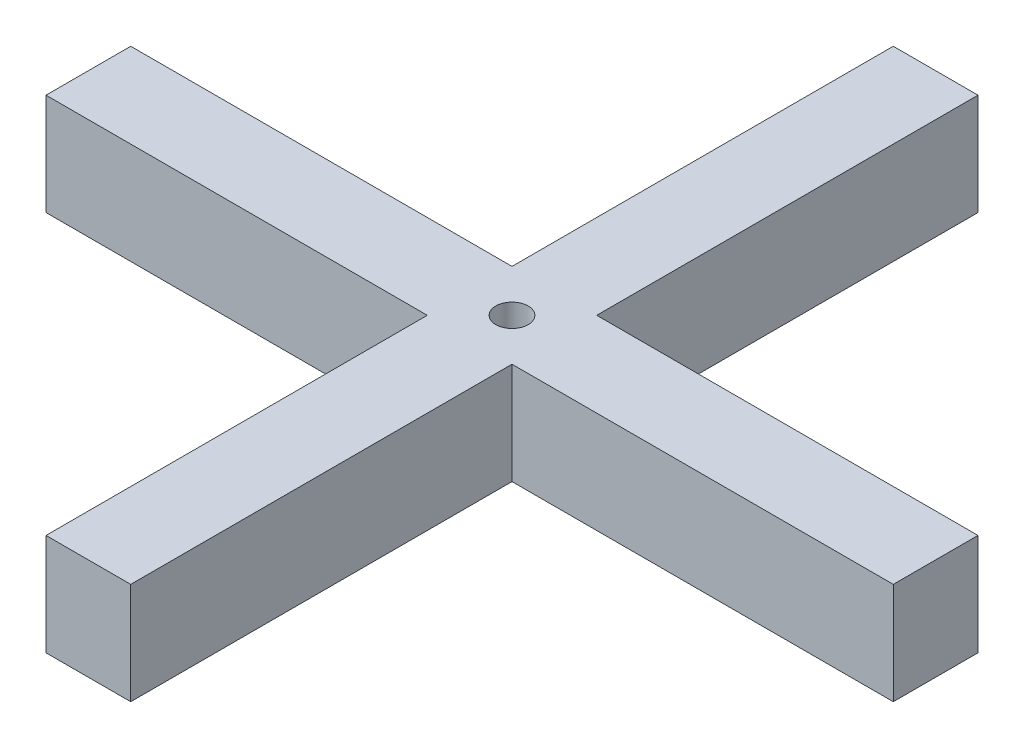
SolidWorks part; units mm, degrees
ref_plane "Front Plane" through (0, 0, 0) normal (0, 0, 1) x (1, 0, 0)
ref_plane "Top Plane" through (0, 0, 0) normal (0, 1, 0) x (1, 0, 0)
ref_plane "Right Plane" through (0, 0, 0) normal (1, 0, 0) x (0, 0, -1)
sketch "Sketch1" plane through (0, 0, 0) normal (0, 1, 0) x (1, 0, 0)
  line L1 (-31.75, 3.175) -> (31.75, 3.175)
  line L2 (-31.75, 3.175) -> (-31.75, -3.175)
  line L3 (-31.75, -3.175) -> (31.75, -3.175)
  line L4 (31.75, 3.175) -> (31.75, -3.175)
  line L5 (-31.75, 3.175) -> (31.75, -3.175) construction
  line L6 (-31.75, -3.175) -> (31.75, 3.175) construction
  line L7 (-3.175, 31.75) -> (3.175, 31.75)
  line L8 (-3.175, 31.75) -> (-3.175, -31.75)
  line L9 (-3.175, -31.75) -> (3.175, -31.75)
  line L10 (3.175, 31.75) -> (3.175, -31.75)
  line L11 (-3.175, 31.75) -> (3.175, -31.75) construction
  line L12 (-3.175, -31.75) -> (3.175, 31.75) construction
  point P0 (0, 0)
  point P6 (0, 0)
  dimension "D1" = 63.5
  dimension "D2" = 6.35
  dimension "D3" = 63.5
  dimension "D4" = 6.35
extrude "Boss-Extrude1" add sketch "Sketch1" along normal blind 7.62 contours L10 L7 L8 L1 | L10 L1 L8 L3 | L10 L3 L8 L9 | L1 L10 L3 L4 | L8 L1 L2 L3
sketch "Sketch2" plane through (0, 7.62, 0) normal (0, 1, 0) x (1, 0, 0)
  circle A0 centre (0, 0) radius 1.2139
  dimension "D1" = 2.4278
extrude "Cut-Extrude1" cut sketch "Sketch2" against normal through all
